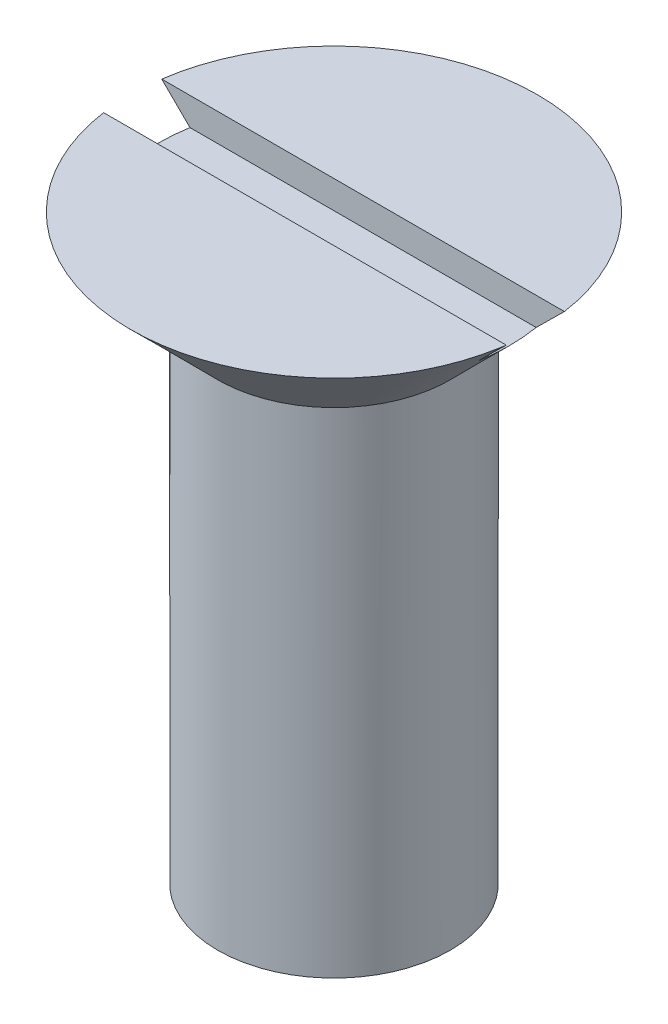
SolidWorks part; units mm, degrees
ref_plane "Front Plane" through (0, 0, 0) normal (0, 0, 1) x (1, 0, 0)
ref_plane "Top Plane" through (0, 0, 0) normal (0, 1, 0) x (1, 0, 0)
ref_plane "Right Plane" through (0, 0, 0) normal (1, 0, 0) x (0, 0, -1)
sketch "Sketch1" plane through (0, 0, 0) normal (0, 0, 1) x (1, 0, 0)
  line L0 (0, 0) -> (0, 17578.591) construction
  line L1 (0, 0) -> (17578.591, 0) construction
  line L2 (0, 0) -> (4, 0)
  line L3 (4, 0) -> (4, 17)
  line L4 (4, 17) -> (7, 20)
  line L5 (7, 20) -> (0, 20)
  line L6 (0, 0) -> (0, 20)
  dimension "D1" = 20
  dimension "D2" = 8
  dimension "D3" = 3
  dimension "D4" = 45
revolve "Revolve1" add sketch "Sketch1" angle 360 about L6
sketch "Sketch2" plane through (0, 20, 0) normal (0, 1, 0) x (1, 0, 0)
  line L1 (-8.0318, -1) -> (8.0318, -1)
  line L2 (-8.0318, -1) -> (-8.0318, 1)
  line L3 (-8.0318, 1) -> (8.0318, 1)
  line L4 (8.0318, -1) -> (8.0318, 1)
  line L5 (-8.0318, -1) -> (8.0318, 1) construction
  line L6 (-8.0318, 1) -> (8.0318, -1) construction
  point P0 (0, 0)
  dimension "D1" = 2
extrude "Cut-Extrude1" cut sketch "Sketch2" against normal blind 0.96
